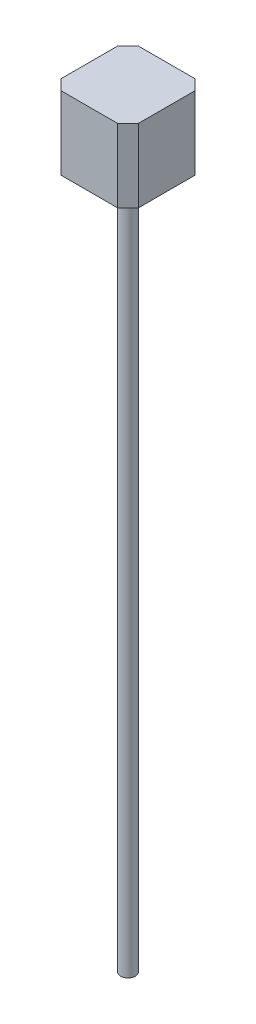
SolidWorks part; units mm, degrees
ref_plane "前视基准面" through (0, 0, 0) normal (0, 0, 1) x (1, 0, 0)
ref_plane "上视基准面" through (0, 0, 0) normal (0, 1, 0) x (1, 0, 0)
ref_plane "右视基准面" through (0, 0, 0) normal (1, 0, 0) x (0, 0, -1)
sketch "草图1" plane through (0, 0, 0) normal (0, 1, 0) x (1, 0, 0)
  circle A0 centre (0, 0) radius 4
  dimension "D1" = 8
extrude "凸台-拉伸1" add sketch "草图1" along normal blind 380
sketch "草图4" plane through (0, 380, 0) normal (0, 1, 0) x (1, 0, 0)
  line L0 (0, 6.8871) -> (0, 4) construction
  line L1 (-0.5288, 3.9649) -> (-0.1847, 4.7932)
  line L2 (0.5288, 3.9649) -> (0.1847, 4.7932)
  line L3 (0.9392, 3.8882) -> (1.5593, 4.5362)
  line L4 (1.9253, 3.5061) -> (1.9037, 4.4028)
  line L5 (2.2804, 3.2863) -> (3.0927, 3.6666)
  line L6 (3.0619, 2.5739) -> (3.3656, 3.4178)
  line L7 (3.3135, 2.2406) -> (4.2084, 2.3018)
  line L8 (3.7849, 1.294) -> (4.373, 1.9712)
  line L9 (3.8992, 0.8923) -> (4.7557, 0.6262)
  line L10 (3.9968, -0.1607) -> (4.7898, 0.2583)
  line L11 (3.9582, -0.5765) -> (4.6608, -1.1341)
  line L12 (3.6688, -1.5936) -> (4.5597, -1.4894)
  line L13 (3.4827, -1.9674) -> (3.9364, -2.7411)
  line L14 (2.8454, -2.8113) -> (3.7137, -3.0359)
  line L15 (2.5368, -3.0927) -> (2.6803, -3.978)
  line L16 (1.6377, -3.6494) -> (2.3663, -4.1725)
  line L17 (1.2483, -3.8002) -> (1.0623, -4.6776)
  line L18 (0.2088, -3.9945) -> (0.6992, -4.7455)
  line L19 (-0.2088, -3.9945) -> (-0.6992, -4.7455)
  line L20 (-1.2483, -3.8002) -> (-1.0623, -4.6776)
  line L21 (-1.6377, -3.6494) -> (-2.3663, -4.1725)
  line L22 (-2.5368, -3.0927) -> (-2.6803, -3.978)
  line L23 (-2.8454, -2.8113) -> (-3.7137, -3.0359)
  line L24 (-3.4827, -1.9674) -> (-3.9364, -2.7411)
  line L25 (-3.6688, -1.5936) -> (-4.5597, -1.4894)
  line L26 (-3.9582, -0.5765) -> (-4.6608, -1.1341)
  line L27 (-3.9968, -0.1607) -> (-4.7898, 0.2583)
  line L28 (-3.8992, 0.8923) -> (-4.7557, 0.6262)
  line L29 (-3.7849, 1.294) -> (-4.373, 1.9712)
  line L30 (-3.3135, 2.2406) -> (-4.2084, 2.3018)
  line L31 (-3.0619, 2.5739) -> (-3.3656, 3.4178)
  line L32 (-2.2804, 3.2863) -> (-3.0927, 3.6666)
  line L33 (-1.9253, 3.5061) -> (-1.9037, 4.4028)
  line L34 (-0.9392, 3.8882) -> (-1.5593, 4.5362)
  circle A0 centre (0, 0) radius 4 construction
  arc A1 (0.5288, 3.9649) -> (-0.5288, 3.9649) centre (0, 0) ccw
  arc A2 (0.1847, 4.7932) -> (-0.1847, 4.7932) centre (0, 4.7165) ccw
  arc A3 (1.9253, 3.5061) -> (0.9392, 3.8882) centre (0, 0) ccw
  arc A4 (1.9037, 4.4028) -> (1.5593, 4.5362) centre (1.7038, 4.398) ccw
  arc A5 (3.0619, 2.5739) -> (2.2804, 3.2863) centre (0, 0) ccw
  arc A6 (3.3656, 3.4178) -> (3.0927, 3.6666) centre (3.1775, 3.4855) ccw
  arc A7 (3.7849, 1.294) -> (3.3135, 2.2406) centre (0, 0) ccw
  arc A8 (4.373, 1.9712) -> (4.2084, 2.3018) centre (4.222, 2.1023) ccw
  arc A9 (3.9968, -0.1607) -> (3.8992, 0.8923) centre (0, 0) ccw
  arc A10 (4.7898, 0.2583) -> (4.7557, 0.6262) centre (4.6963, 0.4352) ccw
  arc A11 (3.6688, -1.5936) -> (3.9582, -0.5765) centre (0, 0) ccw
  arc A12 (4.5597, -1.4894) -> (4.6608, -1.1341) centre (4.5364, -1.2907) ccw
  arc A13 (2.8454, -2.8113) -> (3.4827, -1.9674) centre (0, 0) ccw
  arc A14 (3.7137, -3.0359) -> (3.9364, -2.7411) centre (3.7638, -2.8423) ccw
  arc A15 (1.6377, -3.6494) -> (2.5368, -3.0927) centre (0, 0) ccw
  arc A16 (2.3663, -4.1725) -> (2.6803, -3.978) centre (2.4829, -4.01) ccw
  arc A17 (0.2088, -3.9945) -> (1.2483, -3.8002) centre (0, 0) ccw
  arc A18 (0.6992, -4.7455) -> (1.0623, -4.6776) centre (0.8666, -4.6362) ccw
  arc A19 (-1.2483, -3.8002) -> (-0.2088, -3.9945) centre (0, 0) ccw
  arc A20 (-1.0623, -4.6776) -> (-0.6992, -4.7455) centre (-0.8666, -4.6362) ccw
  arc A21 (-2.5368, -3.0927) -> (-1.6377, -3.6494) centre (0, 0) ccw
  arc A22 (-2.6803, -3.978) -> (-2.3663, -4.1725) centre (-2.4829, -4.01) ccw
  arc A23 (-3.4827, -1.9674) -> (-2.8454, -2.8113) centre (0, 0) ccw
  arc A24 (-3.9364, -2.7411) -> (-3.7137, -3.0359) centre (-3.7638, -2.8423) ccw
  arc A25 (-3.9582, -0.5765) -> (-3.6688, -1.5936) centre (0, 0) ccw
  arc A26 (-4.6608, -1.1341) -> (-4.5597, -1.4894) centre (-4.5364, -1.2907) ccw
  arc A27 (-3.8992, 0.8923) -> (-3.9968, -0.1607) centre (0, 0) ccw
  arc A28 (-4.7557, 0.6262) -> (-4.7898, 0.2583) centre (-4.6963, 0.4352) ccw
  arc A29 (-3.3135, 2.2406) -> (-3.7849, 1.294) centre (0, 0) ccw
  arc A30 (-4.2084, 2.3018) -> (-4.373, 1.9712) centre (-4.222, 2.1023) ccw
  arc A31 (-2.2804, 3.2863) -> (-3.0619, 2.5739) centre (0, 0) ccw
  arc A32 (-3.0927, 3.6666) -> (-3.3656, 3.4178) centre (-3.1775, 3.4855) ccw
  arc A33 (-0.9392, 3.8882) -> (-1.9253, 3.5061) centre (0, 0) ccw
  arc A34 (-1.5593, 4.5362) -> (-1.9037, 4.4028) centre (-1.7038, 4.398) ccw
  point P10 (0, 5.2378)
  point P94 (0, 0)
  dimension "D1" = 0.2
  dimension "D2" = 17
extrude "凸台-拉伸4" [suppressed] add sketch "草图4" against normal blind 3
sketch "草图5" plane through (0, 380, 0) normal (0, 1, 0) x (1, 0, 0)
  line L1 (-21.15, -21.15) -> (21.15, -21.15)
  line L2 (-21.15, -21.15) -> (-21.15, 21.15)
  line L3 (-21.15, 21.15) -> (21.15, 21.15)
  line L4 (21.15, -21.15) -> (21.15, 21.15)
  line L5 (0, 21.15) -> (0, -21.15) construction
  line L6 (-21.15, 0) -> (21.15, 0) construction
  point P0 (0, 0)
  dimension "D1" = 42.3
extrude "凸台-拉伸5" add sketch "草图5" along normal blind 40
sketch "草图7" plane through (0, 420, 0) normal (0, 1, 0) x (1, 0, 0)
  line L0 (-15.5, 21.15) -> (-21.15, 15.5)
  line L1 (21.15, 21.15) -> (-21.15, 21.15) construction
  line L2 (-21.15, 21.15) -> (-21.15, -21.15) construction
  line L3 (21.15, 15.5) -> (15.5, 21.15)
  line L4 (15.5, -21.15) -> (21.15, -15.5)
  line L5 (-21.15, -15.5) -> (-15.5, -21.15)
  line L6 (-21.15, 15.5) -> (-21.15, -15.5)
  line L7 (-15.5, -21.15) -> (15.5, -21.15)
  line L8 (21.15, -15.5) -> (21.15, 15.5)
  line L9 (15.5, 21.15) -> (-15.5, 21.15)
  line L10 (-21.15, -21.15) -> (21.15, -21.15) construction
  point P15 (0, 0)
  dimension "D1" = 4
  dimension "D2" = 31
  dimension "D3" = 135
extrude "切除-拉伸1" cut sketch "草图7" against normal through all flip side to cut
sketch "草图8" plane through (0, 380, 0) normal (0, -1, 0) x (1, 0, 0)
  circle A0 centre (-15.5, 15.5) radius 1.5
  circle A1 centre (15.5, 15.5) radius 1.5
  circle A2 centre (15.5, -15.5) radius 1.5
  circle A3 centre (-15.5, -15.5) radius 1.5
  point P11 (0, 0)
  dimension "D1" = 3
  dimension "D3" = 31
  dimension "D2" = 4
extrude "切除-拉伸2" cut sketch "草图8" against normal blind 4
